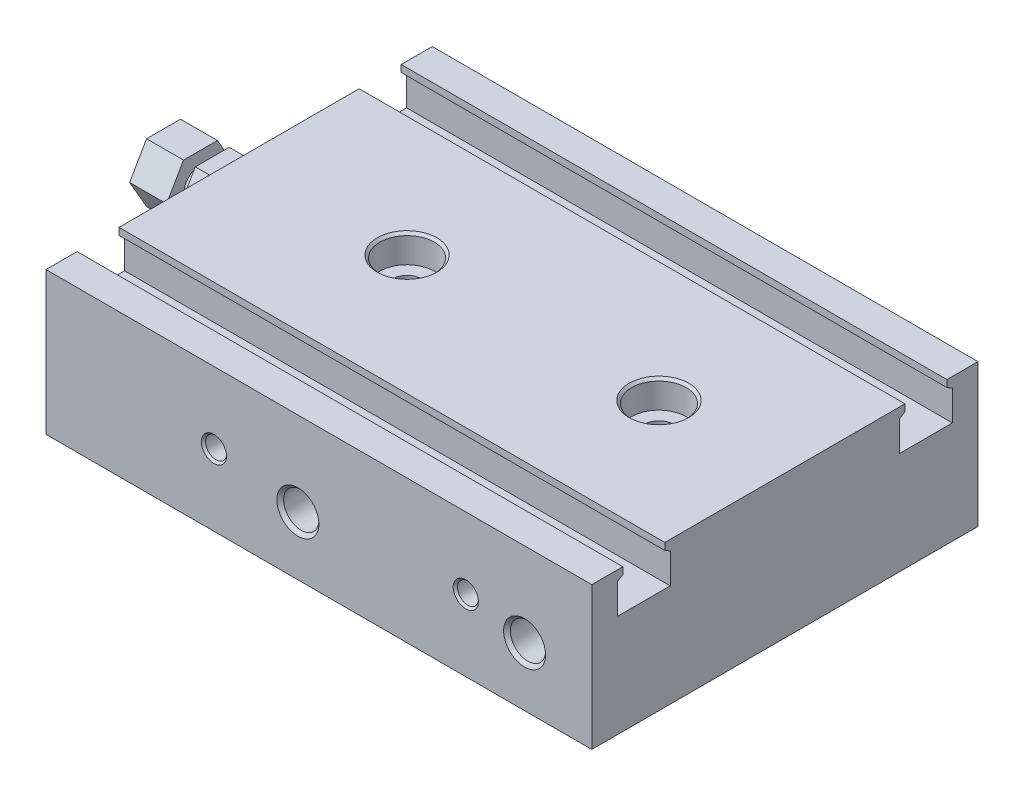
SolidWorks part; units mm, degrees
ref_plane "Plane1" through (0, 0, 0) normal (0, 0, 1) x (1, 0, 0)
ref_plane "Plane2" through (0, 0, 0) normal (0, 1, 0) x (1, 0, 0)
ref_plane "Plane3" through (0, 0, 0) normal (1, 0, 0) x (0, 0, -1)
sketch "Body_Sketch" plane through (0, 0, 0) normal (1, 0, 0) x (0, 0, -1)
  line L0 (-23, 10) -> (-23, -7)
  line L1 (-23, -7) -> (23, -7)
  line L2 (23, -7) -> (23, 10)
  line L3 (23, 10) -> (-23, 10)
  line L4 (-25.3, 0) -> (25.3, 0) construction
  line L5 (0, -7.85) -> (0, 10.85) construction
  line L6 (27.956, 0) -> (-27.956, 0) construction
  line L7 (0, 12.3416) -> (0, -12.3416) construction
  dimension "A" = 46
  dimension "B" = 17
  dimension "QQ" = 7
extrude "Body" add sketch "Body_Sketch" along normal blind 65
sketch "Body Bot Grooves_Sketch" [suppressed] plane through (0, 0, 0) normal (1, 0, 0) x (0, 0, -1)
  line L0 (0, 0) -> (0, -14.4793) construction
  line L1 (-12, -6.5) -> (-4, -6.5)
  line L2 (-4, -6.5) -> (-5, -5.5)
  line L3 (-5, -5.5) -> (-11, -5.5)
  line L4 (-11, -5.5) -> (-12, -6.5)
  line L5 (-8, -5.5) -> (-8, -12.5787) construction
  line L6 (18.5, 10) -> (-18.5, 10) construction
  line L7 (11, -5.5) -> (12, -6.5)
  line L8 (5, -5.5) -> (11, -5.5)
  line L9 (4, -6.5) -> (5, -5.5)
  line L10 (12, -6.5) -> (4, -6.5)
  dimension "Angle" = 45
  dimension "Raw Height" = 16.5
  dimension "Loc Y" = 15.5
  dimension "Width" = 8
  dimension "C2C" = 16
extrude "Body Bot Grooves" [suppressed] cut sketch "Body Bot Grooves_Sketch" along normal through all
sketch "Body Rod Holes_Sketch" plane through (0, 0, 0) normal (-1, 0, 0) x (0, 0, 1)
  line L0 (27.956, 0) -> (-27.956, 0) construction
  line L1 (0, 11.1009) -> (0, -8.2638) construction
  line L2 (0, -12.3416) -> (0, 12.3416) construction
  circle A0 centre (-10, 0) radius 3
  circle A1 centre (10, 0) radius 3
  dimension "NN" = 6
  dimension "H" = 20
extrude "Body Rod Holes" cut sketch "Body Rod Holes_Sketch" against normal blind 10
sketch "Body Piston Holes_Sketch" plane through (10, 0, 0) normal (-1, 0, 0) x (0, 0, 1)
  circle A0 centre (10, 0) radius 4.05
  circle A1 centre (-10, 0) radius 4.05
extrude "Body Piston Holes" cut sketch "Body Piston Holes_Sketch" against normal blind 11
sketch "Body Thru Hole_Sketch" [suppressed] plane through (0, 0, 0) normal (1, 0, 0) x (0, 0, -1)
  line L0 (0, 0) -> (0, -9.4152) construction
  line L1 (11.5, -6) -> (18.5, -6) construction
  circle A0 centre (14.95, -3) radius 1.4
  dimension "Dia" = 2.8
  dimension "Loc Y" = 3
  dimension "Loc Z" = 14.95
extrude "Body Thru Hole" [suppressed] cut sketch "Body Thru Hole_Sketch" along normal through all
sketch "Bot Switch Groove_Sketch" [suppressed] plane through (0, 0, 0) normal (1, 0, 0) x (0, 0, -1)
  line L0 (0, 0) -> (0, -12.0384) construction
  line L1 (1.6, -6.5) -> (-1.6, -6.5)
  line L2 (-1.6, -6.5) -> (-1.6, -3)
  line L3 (-1.6, -3) -> (-2.8, -3)
  line L4 (-2.8, -3) -> (-2.8, 0)
  line L5 (-2.8, 0) -> (2.8, 0)
  line L6 (2.8, -3) -> (2.8, 0)
  line L7 (-12, -6.5) -> (-4, -6.5) construction
  line L8 (1.6, -3) -> (2.8, -3)
  line L10 (1.6, -6.5) -> (1.6, -3)
  point P12 (0, 0)
  point P15 (0, -6.5)
  dimension "Bot Height" = 3.5
  dimension "Top Height" = 3
  dimension "Bot Width" = 3.2
  dimension "Top Width" = 5.6
extrude "Bot Switch Groove" [suppressed] cut sketch "Bot Switch Groove_Sketch" along normal through all
sketch "Top Switch Grooves_Sketch" plane through (0, 0, 0) normal (-1, 0, 0) x (0, 0, 1)
  line L0 (0, -12.3416) -> (0, 12.3416) construction
  line L1 (16.8, 4.6906) -> (16.8, 11.0706) construction
  line L2 (-23, 10) -> (23, 10) construction
  line L3 (13.65, 5.2) -> (19.95, 5.2)
  line L4 (-13.65, 8.8) -> (-13.65, 5.2)
  line L5 (-13.65, 5.2) -> (-19.95, 5.2)
  line L6 (-19.95, 5.2) -> (-19.95, 8.8)
  line L7 (-19.3, 10) -> (-14.3, 10)
  line L8 (19.95, 5.2) -> (19.95, 8.8)
  line L9 (19.3, 9.1753) -> (19.95, 8.8)
  line L10 (19.3, 10) -> (19.3, 9.1753)
  line L11 (19.3, 10) -> (14.3, 10)
  line L12 (-19.3, 10) -> (-19.3, 9.1753)
  line L13 (-14.3, 10) -> (-14.3, 9.1753)
  line L14 (-14.3, 9.1753) -> (-13.65, 8.8)
  line L15 (-19.3, 9.1753) -> (-19.95, 8.8)
  line L16 (0, 4.91) -> (0, 11.29) construction
  line L17 (14.3, 10) -> (14.3, 9.1753)
  line L18 (-16.8, 4.91) -> (-16.8, 11.29) construction
  line L19 (14.3, 9.1753) -> (13.65, 8.8)
  line L20 (13.65, 8.8) -> (13.65, 5.2)
  point P4 (-16.8, 10)
  point P12 (16.8, 10)
  dimension "Bot Width" = 6.3
  dimension "Top Width" = 5
  dimension "P" = 33.6
  dimension "Bot Height" = 3.6
  dimension "Angle" = 120
  dimension "Depth" = 4.8
extrude "Top Switch Grooves" cut sketch "Top Switch Grooves_Sketch" against normal through all
sketch "SHCS MGT Hole_Sketch" plane through (0, 0, 0) normal (0, 0, 1) x (1, 0, 0)
  line L0 (20, 10) -> (16.75, 10)
  line L1 (16.75, 10) -> (16.75, 6.7)
  line L2 (16.75, 6.7) -> (18.3, 6.7)
  line L3 (18.3, 6.7) -> (18.3, -7)
  line L4 (18.3, -7) -> (20, -7)
  line L5 (20, -7) -> (20, 10)
  line L6 (20, -11.5069) -> (20, 12.6548) construction
  line L7 (65, 10) -> (0, 10) construction
  line L8 (65, -7) -> (0, -7) construction
  line L9 (0, -12.5712) -> (0, 12.5712) construction
  dimension "M_depth" = 3.3
  dimension "M" = 6.5
  dimension "U" = 3.4
  dimension "L" = 20
revolve "SHCS MGT Hole" cut sketch "SHCS MGT Hole_Sketch" angle 360 about L6
chamfer "SHCS MGT Hole Cham" distance 0.3 1 edges at (20, 10, -3.25)
pattern_linear "SHCS MGT Hole Pat" count 2 spacing 30 along (1, 0, 0) of "SHCS MGT Hole", "SHCS MGT Hole Cham"
hole_wizard "SHCS MGT Hole Bot Tap" positions "SHCS MGT Hole Bot Tap Loc" profile "SHCS MGT Hole Bot Tap Profile" tap size "M4x0.7" standard "Ansi Metric"
sketch "SHCS MGT Hole Bot Tap Loc" plane through (0, -7, 0) normal (0, -1, 0) x (1, 0, 0)
  circle A0 centre (50, 0) radius 1.7 construction
  circle A1 centre (20, 0) radius 1.7 construction
  point P0 (20, 0)
  point P1 (50, 0)
sketch "SHCS MGT Hole Bot Tap Profile" plane through (20, -7, 0) normal (1, 0, 0) x (0, 0, -1)
  line L0 (0, 0) -> (0, 9.0215)
  line L1 (0, 9.0215) -> (1.7, 8)
  line L2 (1.7, 8) -> (1.7, 7)
  line L3 (1.7, 7) -> (2, 7)
  line L5 (2, 7) -> (2, 0.3)
  line L6 (2, 0.3) -> (2.3, 0)
  line L7 (2.3, 0) -> (0, 0)
  line L8 (-2, 0.3) -> (-2.3, 0) construction
  line L10 (0, 9.0215) -> (-1.7, 8) construction
  line L11 (0, -6.35) -> (0, 107.95) construction
  dimension "Tap Drill Dia." = 3.4
  dimension "Tap Drill Depth" = 8
  dimension "Thread Major Dia." = 4
  dimension "Thread Depth" = 7
  dimension "Near CSink Dia." = 4.6
  dimension "Near CSink Angle" = 90
  dimension "Drill Angle" = 118
sketch "Adjuster Nut_Sketch" plane through (0, 0, 0) normal (-1, 0, 0) x (0, 0, 1)
  line L0 (-2.0207, 8.5) -> (2.0207, 8.5)
  line L1 (2.0207, 8.5) -> (4.0415, 5)
  line L2 (2.0207, 1.5) -> (4.0415, 5)
  line L3 (2.0207, 1.5) -> (-2.0207, 1.5)
  line L4 (-4.0415, 5) -> (-2.0207, 1.5)
  line L5 (-2.0207, 8.5) -> (-4.0415, 5)
  line L6 (0, -12.3416) -> (0, 12.3416) construction
  line L7 (27.956, 0) -> (-27.956, 0) construction
  line L8 (-4.4456, 5) -> (4.4456, 5) construction
  line L10 (0, 1.15) -> (0, 8.85) construction
  circle A0 centre (0, 5) radius 3.5 construction
  dimension "OO_keyw" = 7
  dimension "TT" = 5
extrude "Adjuster Nut" add sketch "Adjuster Nut_Sketch" along normal blind 9
sketch "Adjuster Nut Threads_Sketch" plane through (0, 0, 0) normal (0, 0, 1) x (1, 0, 0)
  line L0 (-4.6, 24) -> (-4.6, 7)
  line L1 (-4.6, 7) -> (-3.2, 7)
  line L2 (-3.2, 7) -> (-3.2, 24)
  line L3 (-3.2, 24) -> (-4.6, 24)
  line L4 (-6.476, 5) -> (-3.044, 5) construction
  line L5 (-9, 5) -> (0, 5) construction
  line L6 (0, -12.5712) -> (0, 12.5712) construction
  line L7 (-9, 5) -> (-9, 8.5) construction
  line L8 (0, 10) -> (0, -7) construction
  dimension "OO" = 4
  dimension "Nut Thickness Body" = 3.2
  dimension "Nut Thickness Plate" = 4.4
revolve "Adjuster Nut Threads" cut sketch "Adjuster Nut Threads_Sketch" angle 360 about L4
hole_wizard "Tap Drill for M5x0.8 Tap1" positions "Sketch2" profile "Sketch1" hole size "M5x0.8" standard "ANSI Metric"
sketch "Sketch2" plane through (0, 0, 23) normal (0, 0, 1) x (1, 0, 0)
  line L0 (65, -7) -> (0, -7) construction
  line L1 (65, 10) -> (65, -7) construction
  line L2 (0, 10) -> (0, -7) construction
  point P0 (30, 0)
  point P2 (57, 0)
  dimension "D1" = 7
  dimension "D2" = 8
  dimension "D3" = 30
sketch "Sketch1" plane through (30, 0, 23) normal (1, 0, 0) x (0, -1, 0)
  line L0 (0, 0) -> (0, 5.7618)
  line L1 (0, 5.7618) -> (2.1, 4.5)
  line L2 (2.1, 4.5) -> (2.1, 0.4)
  line L3 (2.1, 0.4) -> (2.5, 0)
  line L5 (2.5, 0) -> (0, 0)
  line L6 (-2.1, 0.4) -> (-2.5, 0) construction
  line L10 (0, 5.7618) -> (-2.1, 4.5) construction
  line L11 (0, -6.35) -> (0, 107.95) construction
  dimension "Hole Dia." = 4.2
  dimension "Hole Depth" = 4.5
  dimension "Near C'Sink Dia." = 5
  dimension "Near C'Sink Angle" = 90
  dimension "Drill Angle" = 118
hole_wizard "Tap Drill for M5x0.8 Tap2" positions "Sketch4" profile "Sketch3" hole size "M5x0.8" standard "ANSI Metric"
sketch "Sketch4" plane through (0, 0, -23) normal (0, 0, -1) x (-1, 0, 0)
  line L0 (-65, -7) -> (-65, 10) construction
  line L1 (0, -7) -> (0, 10) construction
  line L2 (-65, -7) -> (0, -7) construction
  point P0 (-57, 0)
  point P2 (-30, 0)
  dimension "D1" = 8
  dimension "D2" = 30
  dimension "D3" = 7
sketch "Sketch3" plane through (57, 0, -23) normal (1, 0, 0) x (0, 1, 0)
  line L0 (0, 0) -> (0, 5.7618)
  line L1 (0, 5.7618) -> (2.1, 4.5)
  line L2 (2.1, 4.5) -> (2.1, 0.4)
  line L3 (2.1, 0.4) -> (2.5, 0)
  line L5 (2.5, 0) -> (0, 0)
  line L6 (-2.1, 0.4) -> (-2.5, 0) construction
  line L10 (0, 5.7618) -> (-2.1, 4.5) construction
  line L11 (0, -6.35) -> (0, 107.95) construction
  dimension "Hole Dia." = 4.2
  dimension "Hole Depth" = 4.5
  dimension "Near C'Sink Dia." = 5
  dimension "Near C'Sink Angle" = 90
  dimension "Drill Angle" = 118
hole_wizard "Mount_Holes_1" positions "Sketch6" profile "Sketch5" hole size "M3x0.5" standard "ANSI Metric"
sketch "Sketch6" plane through (0, 0, 23) normal (0, 0, 1) x (1, 0, 0)
  line L0 (65, -7) -> (0, -7) construction
  line L1 (0, 10) -> (0, -7) construction
  point P0 (20, 1.5)
  point P2 (50, 1.5)
  dimension "D1" = 8.5
  dimension "D2" = 20
  dimension "D3" = 30
sketch "Sketch5" plane through (20, 1.5, 23) normal (1, 0, 0) x (0, -1, 0)
  line L0 (0, 0) -> (0, 5.2511)
  line L1 (0, 5.2511) -> (1.25, 4.5)
  line L2 (1.25, 4.5) -> (1.25, 0.25)
  line L3 (1.25, 0.25) -> (1.5, 0)
  line L5 (1.5, 0) -> (0, 0)
  line L6 (-1.25, 0.25) -> (-1.5, 0) construction
  line L10 (0, 5.2511) -> (-1.25, 4.5) construction
  line L11 (0, -6.35) -> (0, 107.95) construction
  dimension "Hole Dia." = 2.5
  dimension "Hole Depth" = 4.5
  dimension "Near C'Sink Dia." = 3
  dimension "Near C'Sink Angle" = 90
  dimension "Drill Angle" = 118
hole_wizard "Mount_Holes_2" positions "Sketch8" profile "Sketch7" hole size "M3x0.5" standard "ANSI Metric"
sketch "Sketch8" plane through (0, 0, -23) normal (0, 0, -1) x (-1, 0, 0)
  line L0 (-65, -7) -> (0, -7) construction
  line L1 (0, -7) -> (0, 10) construction
  point P0 (-50, 1.5)
  point P2 (-20, 1.5)
  dimension "D1" = 8.5
  dimension "D2" = 20
  dimension "D3" = 30
sketch "Sketch7" plane through (50, 1.5, -23) normal (1, 0, 0) x (0, 1, 0)
  line L0 (0, 0) -> (0, 5.2511)
  line L1 (0, 5.2511) -> (1.25, 4.5)
  line L2 (1.25, 4.5) -> (1.25, 0.25)
  line L3 (1.25, 0.25) -> (1.5, 0)
  line L5 (1.5, 0) -> (0, 0)
  line L6 (-1.25, 0.25) -> (-1.5, 0) construction
  line L10 (0, 5.2511) -> (-1.25, 4.5) construction
  line L11 (0, -6.35) -> (0, 107.95) construction
  dimension "Hole Dia." = 2.5
  dimension "Hole Depth" = 4.5
  dimension "Near C'Sink Dia." = 3
  dimension "Near C'Sink Angle" = 90
  dimension "Drill Angle" = 118
hole_wizard "Mount_Holes_3" [suppressed] positions "Sketch10" profile "Sketch9" hole size "M4x0.7" standard "ANSI Metric"
sketch "Sketch10" plane through (0, 0, 49) normal (0, 0, 1) x (1, 0, 0)
  line L0 (182, 19) -> (0, 19) construction
  line L1 (0, 19) -> (0, -19) construction
  point P0 (30, 10)
  point P2 (100, 10)
  dimension "D1" = 7.75
  dimension "D2" = 30
  dimension "D3" = 30
sketch "Sketch9" plane through (30, 10, 49) normal (1, 0, 0) x (0, -1, 0)
  line L0 (0, 0) -> (0, 8.7618)
  line L1 (0, 8.7618) -> (2.1, 7.5)
  line L2 (2.1, 7.5) -> (2.1, 0.4)
  line L3 (2.1, 0.4) -> (2.5, 0)
  line L5 (2.5, 0) -> (0, 0)
  line L6 (-2.1, 0.4) -> (-2.5, 0) construction
  line L10 (0, 8.7618) -> (-2.1, 7.5) construction
  line L11 (0, -6.35) -> (0, 107.95) construction
  dimension "Hole Dia." = 3.3
  dimension "Hole Depth" = 5.5
  dimension "Near C'Sink Dia." = 4
  dimension "Near C'Sink Angle" = 90
  dimension "Drill Angle" = 118
hole_wizard "Mount_Holes_4" [suppressed] positions "Sketch12" profile "Sketch11" hole size "M4x0.7" standard "ANSI Metric"
sketch "Sketch12" plane through (0, 0, -49) normal (0, 0, -1) x (-1, 0, 0)
  line L1 (-182, 19) -> (0, 19) construction
  line L2 (0, -19) -> (0, 19) construction
  point P0 (-100, 10)
  point P2 (-30, 10)
  dimension "D1" = 7.75
  dimension "D2" = 30
  dimension "D3" = 30
sketch "Sketch11" plane through (100, 10, -49) normal (1, 0, 0) x (0, 1, 0)
  line L0 (0, 0) -> (0, 8.7618)
  line L1 (0, 8.7618) -> (2.1, 7.5)
  line L2 (2.1, 7.5) -> (2.1, 0.4)
  line L3 (2.1, 0.4) -> (2.5, 0)
  line L5 (2.5, 0) -> (0, 0)
  line L6 (-2.1, 0.4) -> (-2.5, 0) construction
  line L10 (0, 8.7618) -> (-2.1, 7.5) construction
  line L11 (0, -6.35) -> (0, 107.95) construction
  dimension "Hole Dia." = 3.3
  dimension "Hole Depth" = 5.5
  dimension "Near C'Sink Dia." = 4
  dimension "Near C'Sink Angle" = 90
  dimension "Drill Angle" = 118
hole_wizard "1/8 Rc Tapped Hole1" [suppressed] positions "Sketch14" profile "Sketch13" size "1/8" standard "ISO"
sketch "Sketch14" plane through (0, 0, 49) normal (0, 0, 1) x (1, 0, 0)
  line L0 (182, -19) -> (0, -19) construction
  line L1 (0, 19) -> (0, -19) construction
  line L2 (182, 19) -> (182, -19) construction
  point P0 (56, 0)
  point P2 (172, 0)
  dimension "D1" = 15
  dimension "D2" = 46
  dimension "D3" = 9
sketch "Sketch13" plane through (56, 0, 49) normal (1, 0, 0) x (0, -1, 0)
  line L0 (0, 0) -> (0, 11.4134)
  line L1 (3.95, 9.04) -> (0, 11.4134)
  line L2 (-3.95, 9.04) -> (0, 11.4134) construction
  line L3 (3.95, 9.04) -> (3.95, 4.5)
  line L4 (3.95, 4.5) -> (4.633, 4.5)
  line L5 (4.633, 4.5) -> (4.7735, 0)
  line L6 (-4.633, 4.5) -> (-4.7735, 0) construction
  line L7 (4.7735, 0) -> (0, 0)
  line L8 (0, -6.35) -> (0, 107.95) construction
  line L11 (-3.95, 4.5) -> (-4.633, 4.5) construction
  dimension "Tap Drill Dia." = 7.9
  dimension "Tap Drill Depth" = 9.04
  dimension "Thread Dia." = 9.5469
  dimension "Thread Angle" = 3.576
  dimension "Thread Depth" = 4.5
  dimension "Drill Angle" = 118
hole_wizard "1/8 Rc Tapped Hole2" [suppressed] positions "Sketch16" profile "Sketch15" size "1/8" standard "ISO"
sketch "Sketch16" plane through (0, 0, -49) normal (0, 0, -1) x (-1, 0, 0)
  line L0 (-182, -19) -> (0, -19) construction
  line L1 (0, -19) -> (0, 19) construction
  line L2 (-182, -19) -> (-182, 19) construction
  point P0 (-172, 0)
  point P2 (-56, 0)
  dimension "D1" = 15
  dimension "D2" = 46
  dimension "D3" = 9
sketch "Sketch15" plane through (172, 0, -49) normal (1, 0, 0) x (0, 1, 0)
  line L0 (0, 0) -> (0, 11.4134)
  line L1 (3.95, 9.04) -> (0, 11.4134)
  line L2 (-3.95, 9.04) -> (0, 11.4134) construction
  line L3 (3.95, 9.04) -> (3.95, 4.5)
  line L4 (3.95, 4.5) -> (4.633, 4.5)
  line L5 (4.633, 4.5) -> (4.7735, 0)
  line L6 (-4.633, 4.5) -> (-4.7735, 0) construction
  line L7 (4.7735, 0) -> (0, 0)
  line L8 (0, -6.35) -> (0, 107.95) construction
  line L11 (-3.95, 4.5) -> (-4.633, 4.5) construction
  dimension "Tap Drill Dia." = 7.9
  dimension "Tap Drill Depth" = 9.04
  dimension "Thread Dia." = 9.5469
  dimension "Thread Angle" = 3.576
  dimension "Thread Depth" = 4.5
  dimension "Drill Angle" = 118
